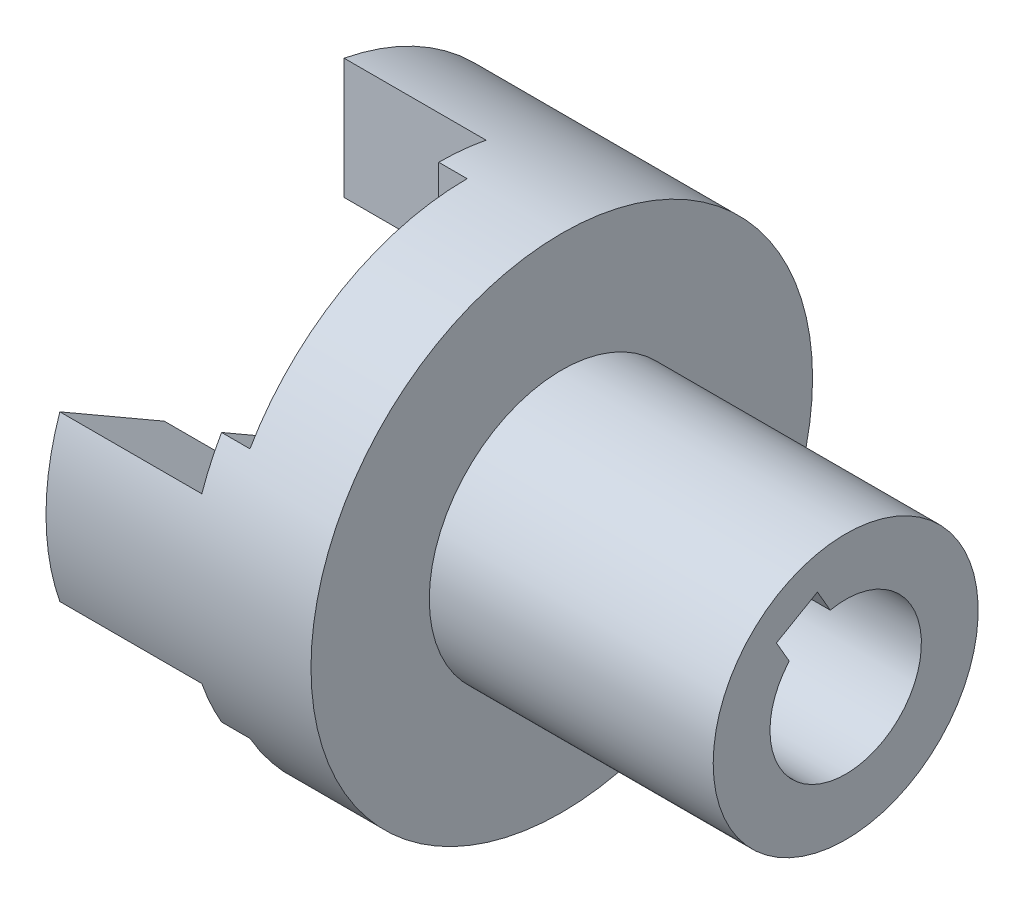
SolidWorks part; units mm, degrees
ref_plane "Спереди" through (0, 0, 0) normal (0, 0, 1) x (1, 0, 0)
ref_plane "Сверху" through (0, 0, 0) normal (0, 1, 0) x (1, 0, 0)
ref_plane "Справа" through (0, 0, 0) normal (1, 0, 0) x (0, 0, -1)
sketch "Эскиз1" plane through (0, 0, 0) normal (0, 0, 1) x (1, 0, 0)
  line L0 (0, 0) -> (61.9747, 0) construction
  line L1 (0, 8) -> (0, 26.5)
  line L2 (10, 26.5) -> (0, 26.5)
  line L3 (10, 26.5) -> (10, 14)
  line L4 (10, 14) -> (40, 14)
  line L5 (40, 14) -> (40, 8)
  line L6 (0, 8) -> (40, 8)
  dimension "d" = 16
  dimension "l" = 40
  dimension "l3" = 10
  dimension "DD" = 53
  dimension "d1" = 28
revolve "Повернуть1" add sketch "Эскиз1" angle 360 about L0
sketch "Эскиз2" plane through (0, 0, 0) normal (-1, 0, 0) x (0, 0, 1)
  line L7 (22.9497, 13.25) -> (14, 8.0829)
  line L14 (14, -8.0829) -> (22.9497, -13.25)
  line L15 (14, 8.0829) -> (14, -8.0829)
  circle A0 centre (0, 0) radius 26.5 construction
  arc A1 (22.9497, 13.25) -> (22.9497, -13.25) centre (0, 0) cw
  dimension "D1" = 120
  dimension "D2" = 120
  dimension "D3" = 14
extrude "Бобышка-Вытянуть1" add sketch "Эскиз2" along normal blind 3
sketch "Эскиз3" plane through (-3, 0, 0) normal (-1, 0, 0) x (0, 0, 1)
  line L0 (25.0375, 8.6819) -> (14, 2.3094)
  line L1 (14, 8.0829) -> (14, -8.0829) construction
  line L2 (14, 2.3094) -> (14, -2.3094)
  line L3 (14, -2.3094) -> (25.0375, -8.6819)
  line L9 (14, -8.0829) -> (22.9497, -13.25) construction
  arc A1 (22.9497, -13.25) -> (22.9497, 13.25) centre (0, 0) ccw construction
  arc A2 (25.0375, 8.6819) -> (25.0375, -8.6819) centre (0, 0) cw
  dimension "D1" = 120
  dimension "B" = 5
other "Выровнять группу1"
extrude "Бобышка-Вытянуть2" add sketch "Эскиз3" along normal blind 15
pattern_circular "Круговой массив1" count 3 over 360 about axis through (0, 0, 0) along (1, 0, 0) of "Бобышка-Вытянуть2", "Бобышка-Вытянуть1"
sketch "Эскиз4" plane through (40, 0, 0) normal (1, 0, 0) x (0, 0, -1)
  line L0 (0, 0) -> (-9.5718, 16.5788) construction
  line L1 (0, 0) -> (0, 18.6166) construction
  line L2 (-7.3151, 7.6701) -> (-2.9849, 10.1701)
  line L3 (-2.9849, 10.1701) -> (2.1651, 1.25)
  line L4 (2.1651, 1.25) -> (-2.1651, -1.25)
  line L5 (-2.1651, -1.25) -> (-7.3151, 7.6701)
  dimension "D1" = 30
  dimension "b" = 5
  dimension "(d/2)+t1" = 10.3
extrude "Вырез-Вытянуть1" cut sketch "Эскиз4" against normal through all
